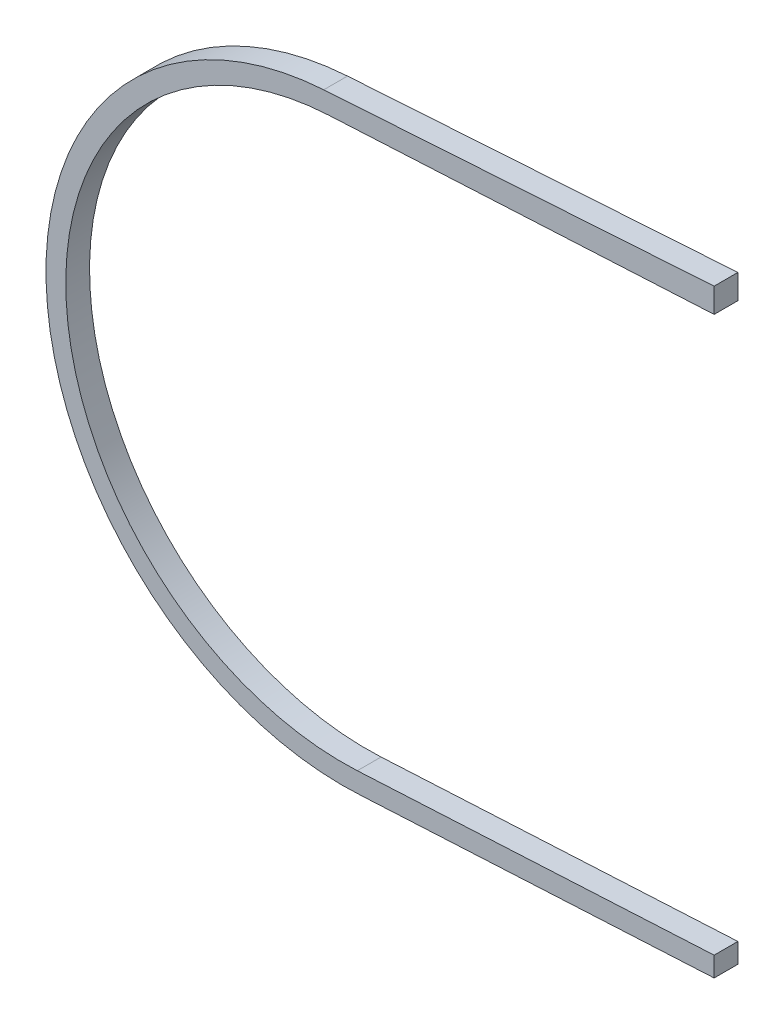
SolidWorks part; units mm, degrees
ref_plane "Front Plane" through (0, 0, 0) normal (0, 0, 1) x (1, 0, 0)
ref_plane "Top Plane" through (0, 0, 0) normal (0, 1, 0) x (1, 0, 0)
ref_plane "Right Plane" through (0, 0, 0) normal (1, 0, 0) x (0, 0, -1)
sketch "Sketch1" plane through (0, 0, 0) normal (0, 0, 1) x (1, 0, 0)
  line L0 (-4.8231, 74.8448) -> (93.8097, 81.2008)
  line L1 (-3.6619, 69.9042) -> (93.8097, 75.0101)
  line L2 (3.6619, -69.9042) -> (93.8097, -65.1818)
  line L3 (4.8231, -74.8448) -> (93.8097, -70.1832)
  line L4 (93.8097, 81.2008) -> (93.8097, 75.0101)
  line L5 (93.8097, -65.1818) -> (93.8097, -70.1832)
  arc A0 (-3.6619, 69.9042) -> (3.6619, -69.9042) centre (0, 0) ccw
  arc A1 (-4.8231, 74.8448) -> (4.8231, -74.8448) centre (0, 0) ccw
  dimension "D1" = 70
  dimension "D2" = 75
extrude "Boss-Extrude1" add sketch "Sketch1" along normal blind 6
